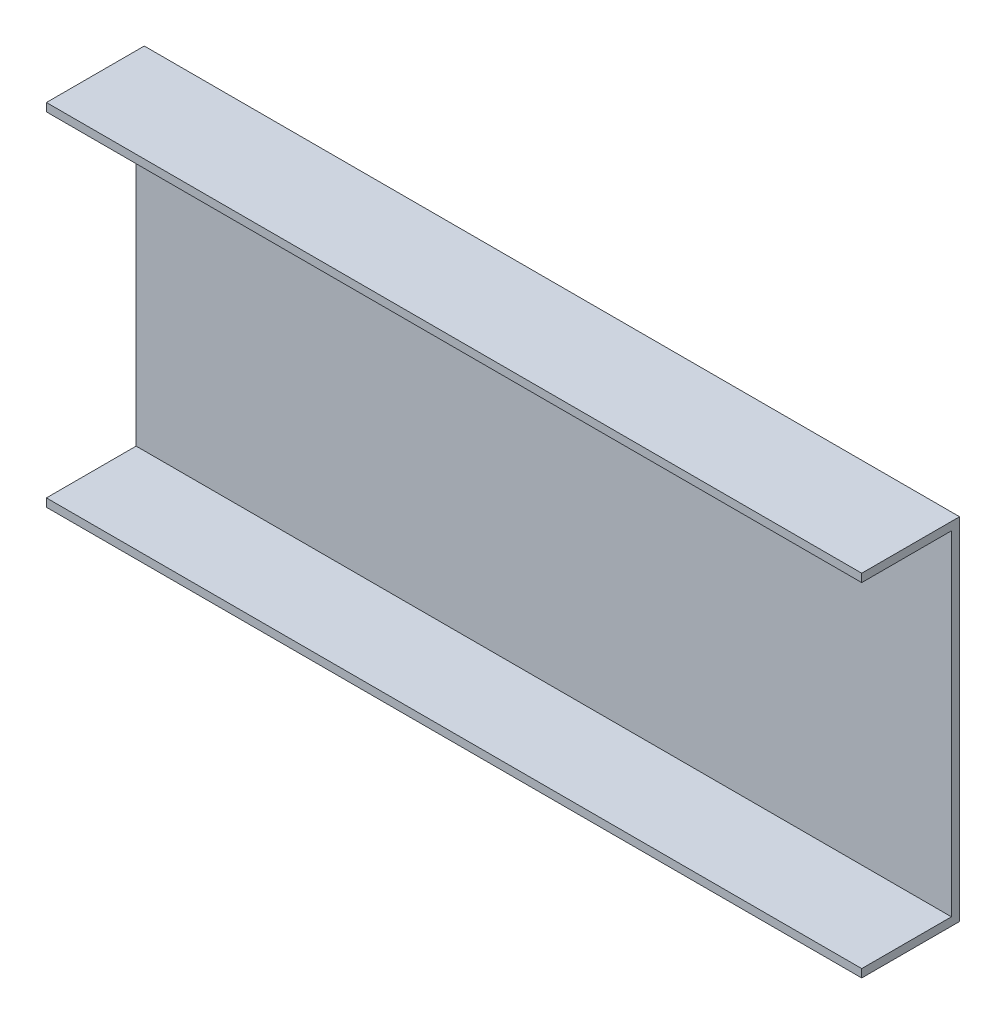
SolidWorks part; units mm, degrees
ref_plane "前视基准面" through (0, 0, 0) normal (0, 0, 1) x (1, 0, 0)
ref_plane "上视基准面" through (0, 0, 0) normal (0, 1, 0) x (1, 0, 0)
ref_plane "右视基准面" through (0, 0, 0) normal (1, 0, 0) x (0, 0, -1)
sketch "草图1" plane through (0, 0, 0) normal (0, 0, 1) x (1, 0, 0)
  line L1 (0, 0) -> (100, 0)
  line L2 (0, 0) -> (0, -43)
  line L3 (0, -43) -> (100, -43)
  line L4 (100, 0) -> (100, -43)
  dimension "D1" = 100
  dimension "D2" = 43
extrude "凸台-拉伸1" add sketch "草图1" along normal blind 12
sketch "草图2" plane through (0, 0, 12) normal (0, 0, 1) x (1, 0, 0)
  line L0 (0, 0) -> (0, -43) construction
  line L1 (0, -1) -> (100, -1)
  line L2 (0, -1) -> (0, -42)
  line L3 (0, -42) -> (100, -42)
  line L4 (100, -1) -> (100, -42)
  line L5 (100, -43) -> (100, 0) construction
  line L6 (100, 0) -> (0, 0) construction
  line L7 (0, -43) -> (100, -43) construction
  dimension "D1" = 1
  dimension "D2" = 1
extrude "切除-拉伸1" cut sketch "草图2" against normal blind 11
